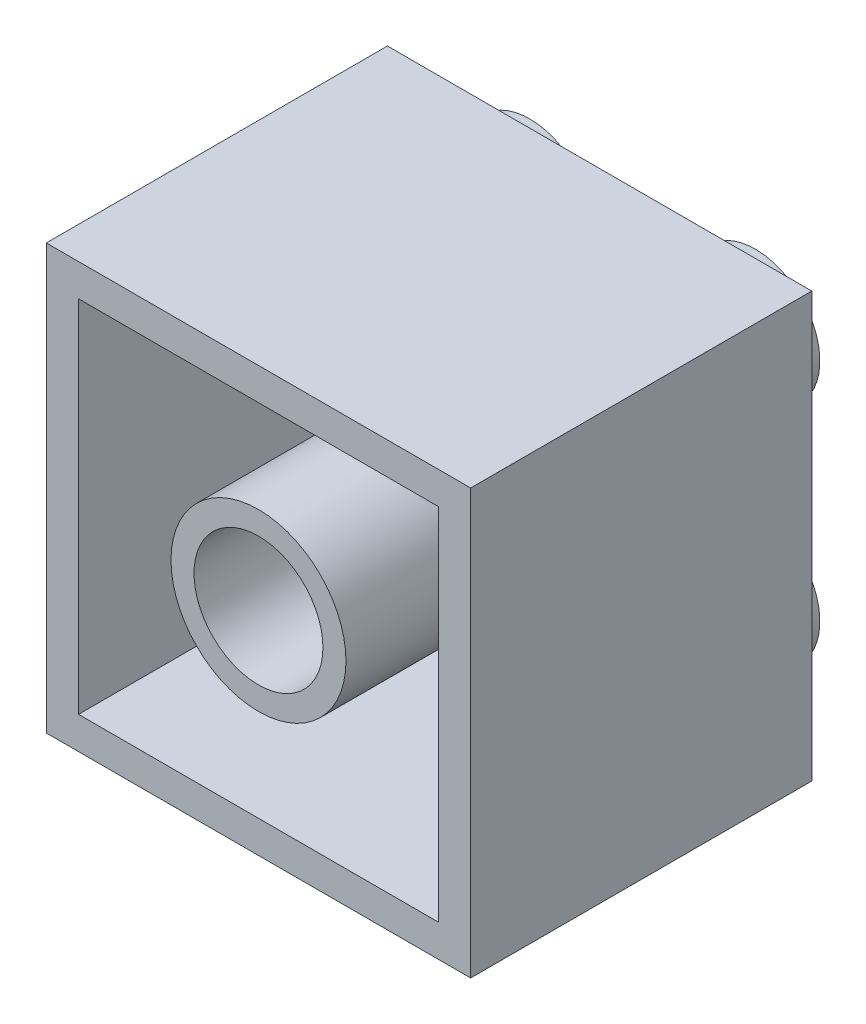
SolidWorks part; units mm, degrees
ref_plane "Front Plane" through (0, 0, 0) normal (1, 0, 0) x (0, 1, 0)
ref_plane "Top Plane" through (0, 0, 0) normal (0, 0, 1) x (0, 1, 0)
ref_plane "Right Plane" through (0, 0, 0) normal (0, 1, 0) x (-1, 0, 0)
sketch "Sketch2" plane through (0, 0, 0) normal (0, 0, 1) x (0, 1, 0)
  line L1 (-7.9, -7.9) -> (7.9, -7.9)
  line L2 (-7.9, -7.9) -> (-7.9, 7.9)
  line L3 (-7.9, 7.9) -> (7.9, 7.9)
  line L4 (7.9, -7.9) -> (7.9, 7.9)
  line L5 (-7.9, -7.9) -> (7.9, 7.9) construction
  line L6 (-7.9, 7.9) -> (7.9, -7.9) construction
  point P0 (0, 0)
  dimension "D1" = 15.8
  dimension "D2" = 15.8
extrude "Boss-Extrude1" add sketch "Sketch2" along normal blind 12.7
sketch3d "3DSketch1"
  line L0 (-6.7, -6.7, 12.7) -> (6.7, -6.7, 12.7)
  line L1 (6.7, -6.7, 12.7) -> (6.7, 6.7, 12.7)
  line L2 (6.7, 6.7, 12.7) -> (-6.7, 6.7, 12.7)
  line L3 (-6.7, 6.7, 12.7) -> (-6.7, -6.7, 12.7)
  line L4 (-6.7, -6.7, 12.7) -> (6.7, -6.7, 12.7)
  line L5 (6.7, -6.7, 12.7) -> (6.7, 6.7, 12.7)
  line L6 (6.7, 6.7, 12.7) -> (-6.7, 6.7, 12.7)
  line L7 (-6.7, 6.7, 12.7) -> (-6.7, -6.7, 12.7)
  line L8 (7.9, -7.9, 12.7) -> (7.9, 7.9, 12.7) construction
  dimension "D2" = 1.2
  dimension "D1" = 1.2
extrude "Cut-Extrude1" cut sketch "3DSketch1" along direction (0, 0, -1) on the side against the normal blind 11.5 contours L7 L4 L5 L6
sketch "Sketch4" plane through (0, 0, 0) normal (0, 0, -1) x (1, 0, 0)
  line L0 (-7.9, -7.9) -> (-7.9, 7.9) construction
  line L1 (7.9, -7.9) -> (-7.9, -7.9) construction
  line L2 (-7.9, 0) -> (7.9, 0) construction
  line L3 (7.9, 7.9) -> (7.9, -7.9) construction
  line L4 (-7.9, 7.9) -> (7.9, 7.9) construction
  line L5 (0, 7.9) -> (0, -7.9) construction
  circle A0 centre (-4.2, -4.2) radius 2.4
  circle A3 centre (-4.2, 4.2) radius 2.4
  circle A4 centre (4.2, -4.2) radius 2.4
  circle A5 centre (4.2, 4.2) radius 2.4
  circle A6 centre (-4.2, 4.2) radius 2.4
  dimension "D1" = 4.8
  dimension "D2" = 3.7
  dimension "D3" = 3.7
  dimension "D6" = 7.9
sketch "Sketch5" plane through (0, 0, 1.2) normal (0, 0, 1) x (1, 0, 0)
  circle A0 centre (0, 0) radius 3.2569
  circle A1 centre (0, 0) radius 2.4
  dimension "D1" = 6.5137
  dimension "D2" = 4.8
extrude "Boss-Extrude3" add sketch "Sketch5" along normal blind 11.5 contours A0
sketch "Sketch6" plane through (0, 0, 12.7) normal (0, 0, 1) x (1, 0, 0)
  circle A0 centre (0, 0) radius 2.4
  dimension "D1" = 4.8
extrude "Cut-Extrude2" cut sketch "Sketch6" against normal blind 11.5
sketch "Sketch7" plane through (0, 0, 1.2) normal (0, 0, 1) x (1, 0, 0)
  line L0 (6.7, 6.7) -> (-6.7, 6.7) construction
  line L1 (-6.7, 6.7) -> (-6.7, -6.7) construction
  line L2 (0, 6.7) -> (0, -6.7) construction
  line L3 (-6.7, -6.7) -> (6.7, -6.7) construction
  line L4 (-6.7, 0) -> (6.7, 0) construction
  line L5 (-6.7, 6.7) -> (-6.7, -6.7) construction
  line L6 (6.7, -6.7) -> (6.7, 6.7) construction
  circle A0 centre (-4.3, 4.3) radius 1.2
  circle A1 centre (4.3, 4.3) radius 1.2
  circle A2 centre (4.3, -4.3) radius 1.2
  circle A3 centre (-4.3, -4.3) radius 1.2
  dimension "D1" = 2.4
  dimension "D2" = 2.4
  dimension "D3" = 2.4
extrude "Boss-Extrude4" add sketch "Sketch4" along normal blind 1.6 contours A3 | A5 | A0 | A4
extrude "Cut-Extrude3" cut sketch "Sketch7" against normal blind 1.6 contours A3 | A0 | A2 | A1
sketch "Sketch8" plane through (-7.9, 0, 0) normal (-1, 0, 0) x (0, -1, 0)
  line L0 (7.9, 6.35) -> (-7.9, 6.35) construction
  line L3 (-7.9, 12.7) -> (-7.9, 0) construction
  line L4 (0.3224, 4.35) -> (0.3224, 7.55)
  line L5 (0.3224, 7.55) -> (-0.8776, 7.55)
  line L6 (-0.8776, 7.55) -> (-0.8776, 8.35)
  line L7 (-0.8776, 8.35) -> (1.1224, 8.35)
  line L8 (1.1224, 8.35) -> (1.1224, 4.35)
  line L9 (1.1224, 4.35) -> (0.3224, 4.35)
  point P0 (0, 6.35)
  point P3 (7.9, 6.35)
  dimension "D1" = 1.2
  dimension "D2" = 0.8
  dimension "D3" = 2
  dimension "D4" = 1.2
  dimension "D5" = 4
extrude "Cut-Extrude4" cut sketch "Sketch8" against normal blind 0.4
